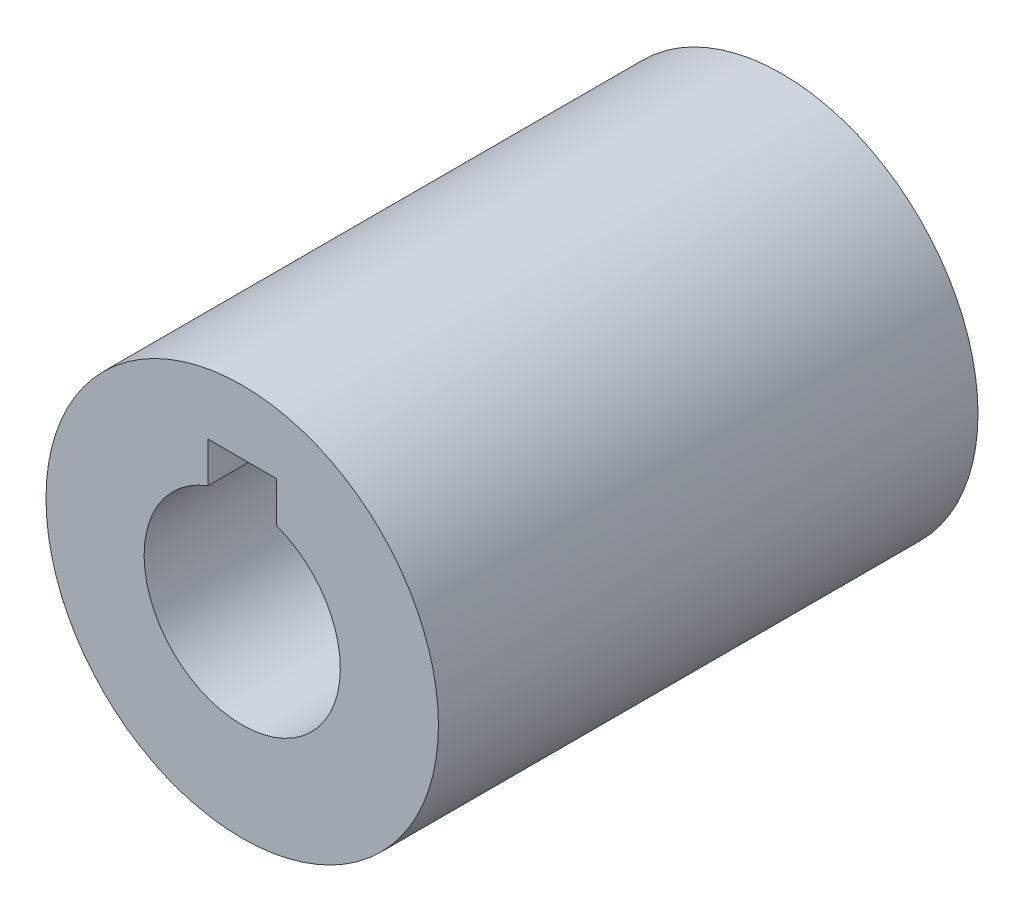
SolidWorks part; units mm, degrees
ref_plane "Спереди" through (0, 0, 0) normal (0, 0, 1) x (1, 0, 0)
ref_plane "Сверху" through (0, 0, 0) normal (0, 1, 0) x (1, 0, 0)
ref_plane "Справа" through (0, 0, 0) normal (1, 0, 0) x (0, 0, -1)
sketch "Эскиз1" plane through (0, 0, 0) normal (0, 0, 1) x (1, 0, 0)
  line L0 (0, 0) -> (0, 20) construction
  line L2 (-3.5, -1.5) -> (3.5, -1.5)
  line L3 (-3.5, -1.5) -> (-3.5, 13.5)
  line L4 (-3.5, 13.5) -> (3.5, 13.5)
  line L5 (3.5, -1.5) -> (3.5, 13.5)
  line L6 (-3.5, -1.5) -> (3.5, 13.5) construction
  line L7 (-3.5, 13.5) -> (3.5, -1.5) construction
  circle A0 centre (0, 0) radius 20
  circle A1 centre (0, 0) radius 10
  point P4 (0, 6)
  dimension "D1" = 40
  dimension "D2" = 20
  dimension "D3" = 6
  dimension "D4" = 15
  dimension "D5" = 7
extrude "Бобышка-Вытянуть1" add sketch "Эскиз1" along normal blind 55 contours A0 A1 L3 L4 L5
